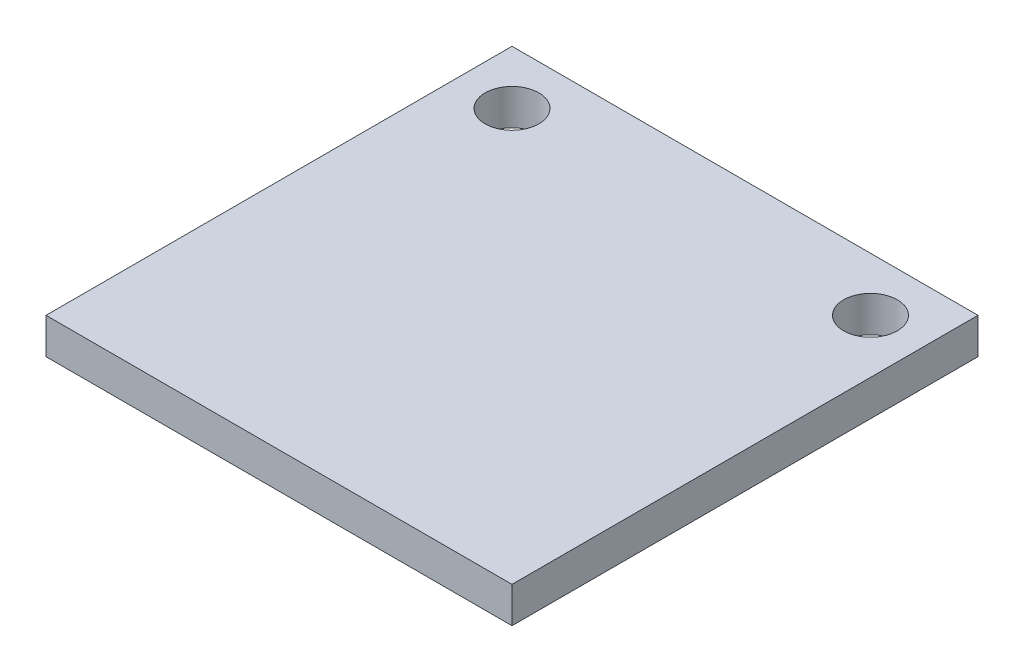
SolidWorks part; units mm, degrees
ref_plane "Front Plane" through (0, 0, 0) normal (0, 0, 1) x (1, 0, 0)
ref_plane "Top Plane" through (0, 0, 0) normal (0, 1, 0) x (1, 0, 0)
ref_plane "Right Plane" through (0, 0, 0) normal (1, 0, 0) x (0, 0, -1)
sketch "Sketch1" plane through (0, 0, 0) normal (0, 1, 0) x (1, 0, 0)
  line L1 (-13, -13) -> (13, -13)
  line L2 (-13, -13) -> (-13, 13)
  line L3 (-13, 13) -> (13, 13)
  line L4 (13, -13) -> (13, 13)
  line L5 (-13, -13) -> (13, 13) construction
  line L6 (-13, 13) -> (13, -13) construction
  circle A0 centre (-10, 10) radius 1.5
  circle A1 centre (10, 10) radius 1.5
  point P0 (0, 0)
  dimension "D2" = 3
  dimension "D3" = 3
  dimension "D1" = 26
  dimension "D4" = 20
extrude "Boss-Extrude1" add sketch "Sketch1" along normal blind 2
